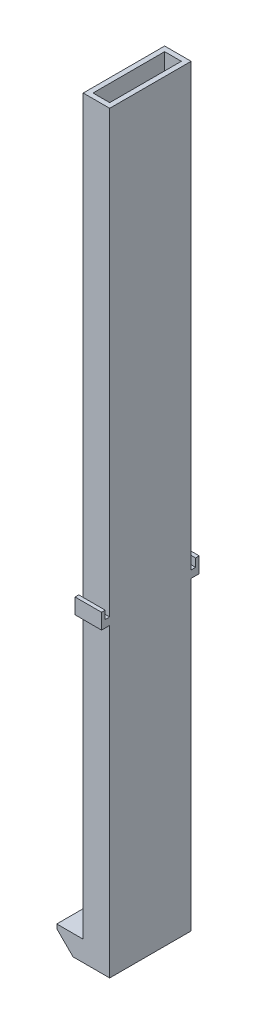
SolidWorks part; units mm, degrees
ref_plane "Front Plane" through (0, 0, 0) normal (0, 0, 1) x (1, 0, 0)
ref_plane "Top Plane" through (0, 0, 0) normal (0, 1, 0) x (1, 0, 0)
ref_plane "Right Plane" through (0, 0, 0) normal (1, 0, 0) x (0, 0, -1)
sketch "Sketch1" plane through (0, 0, 0) normal (0, 0, 1) x (1, 0, 0)
  line L1 (-3.25, -46.25) -> (3.25, -46.25)
  line L2 (-3.25, -46.25) -> (-3.25, 46.25)
  line L3 (-3.25, 46.25) -> (3.25, 46.25)
  line L4 (3.25, -46.25) -> (3.25, 46.25)
  line L5 (-3.25, -46.25) -> (3.25, 46.25) construction
  line L6 (-3.25, 46.25) -> (3.25, -46.25) construction
  point P0 (0, 0)
  dimension "D1" = 6.5
  dimension "D2" = 92.5
extrude "Boss-Extrude1" add sketch "Sketch1" along normal blind 10 contours L3 L4 L1 L2
sketch "Sketch2" plane through (0, 0, 10) normal (0, 0, 1) x (1, 0, 0)
  line L0 (-3.25, -46.25) -> (3.25, -46.25) construction
  line L1 (-3.25, 46.25) -> (0, 46.25)
  line L2 (-3.25, 46.25) -> (-3.25, -43.75)
  line L3 (-3.25, -43.75) -> (0, -43.75)
  line L4 (0, 46.25) -> (0, -43.75)
  dimension "D1" = 2.5
extrude "Cut-Extrude1" cut sketch "Sketch2" against normal blind 10
chamfer "Chamfer1" distance 2 1 edges at (-3.25, -46.25, 5)
sketch "Sketch4" plane through (0, 0, 0) normal (-1, 0, 0) x (0, 0, 1)
  line L1 (10, -43.75) -> (10, 46.25) construction
  line L2 (10, -8.75) -> (11, -8.75)
  line L3 (11, -8.75) -> (11, -6.85)
  line L4 (11, -6.85) -> (10.55, -6.85)
  line L5 (10, -8.75) -> (10, -7.85)
  line L6 (10, -7.85) -> (10.55, -7.85)
  line L7 (10.55, -7.85) -> (10.55, -6.85)
  dimension "D1" = 37.5
  dimension "D2" = 1
  dimension "D3" = 1.9
  dimension "D4" = 0.45
  dimension "D5" = 0.9
extrude "Boss-Extrude2" add sketch "Sketch4" against normal blind 3.25 contours L3 L4 L7 L6 L5 L2
ref_plane "Plane1" through (0, 0, 5) normal (0, 0, 1) x (1, 0, 0)
mirror "Mirror1" about plane through (0, 0, 5) normal (0, 0, 1) of "Boss-Extrude2"
sketch "Sketch6" plane through (0, 46.25, 0) normal (0, 1, 0) x (1, 0, 0)
  line L0 (1.625, 0) -> (1.625, -10) construction
  line L3 (0, -5) -> (3.25, -5) construction
  line L4 (0, 0) -> (0, -10) construction
  line L5 (3.25, -10) -> (3.25, 0) construction
  line L6 (0, 0) -> (3.25, 0) construction
  line L7 (0, -10) -> (3.25, -10) construction
  line L9 (0.6, -9.4) -> (2.65, -9.4)
  line L10 (0.6, -9.4) -> (0.6, -0.6)
  line L11 (0.6, -0.6) -> (2.65, -0.6)
  line L12 (2.65, -9.4) -> (2.65, -0.6)
  line L13 (0.6, -9.4) -> (2.65, -0.6) construction
  line L14 (0.6, -0.6) -> (2.65, -9.4) construction
  point P12 (1.625, -5)
  dimension "D1" = 0.6
  dimension "D2" = 0.6
extrude "Cut-Extrude2" cut sketch "Sketch6" against normal blind 80
